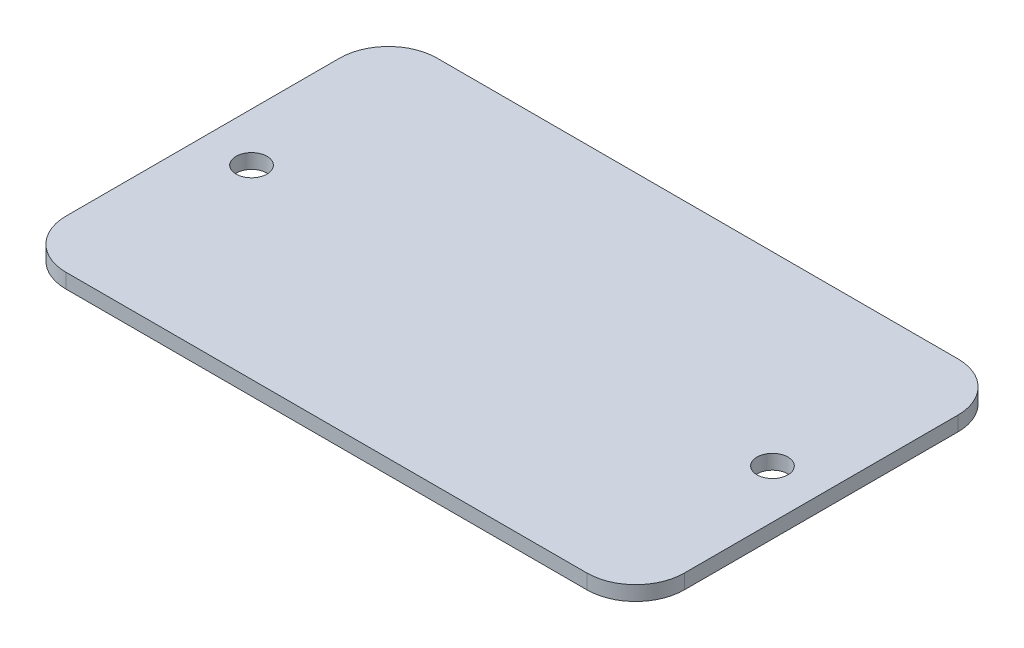
SolidWorks part; units mm, degrees
ref_plane "Front Plane" through (0, 0, 0) normal (0, 0, 1) x (1, 0, 0)
ref_plane "Top Plane" through (0, 0, 0) normal (0, 1, 0) x (1, 0, 0)
ref_plane "Right Plane" through (0, 0, 0) normal (1, 0, 0) x (0, 0, -1)
sketch "Sketch1" plane through (0, 0, 0) normal (0, 1, 0) x (1, 0, 0)
  line L1 (-53.5, -38.1) -> (53.5, -38.1)
  line L2 (-63.5, -28.1) -> (-63.5, 28.1)
  line L3 (-53.5, 38.1) -> (53.5, 38.1)
  line L4 (63.5, -28.1) -> (63.5, 28.1)
  line L5 (-63.5, -38.1) -> (63.5, 38.1) construction
  line L6 (-63.5, 38.1) -> (63.5, -38.1) construction
  arc A0 (53.5, 38.1) -> (63.5, 28.1) centre (53.5, 28.1) cw
  arc A1 (-53.5, -38.1) -> (-63.5, -28.1) centre (-53.5, -28.1) cw
  arc A2 (53.5, -38.1) -> (63.5, -28.1) centre (53.5, -28.1) ccw
  arc A3 (-63.5, 28.1) -> (-53.5, 38.1) centre (-53.5, 28.1) cw
  point P0 (0, 0)
  dimension "D3" = 10
  dimension "D1" = 127
  dimension "D2" = 76.2
extrude "Boss-Extrude1" add sketch "Sketch1" along normal blind 3
sketch "Sketch2" plane through (0, 3, 0) normal (0, 1, 0) x (1, 0, 0)
  line L0 (63.5, -28.1) -> (63.5, 28.1) construction
  line L1 (-63.5, 28.1) -> (-63.5, -28.1) construction
  circle A0 centre (-53.5, 0) radius 3.175
  circle A1 centre (53.5, 0) radius 3.175
  dimension "D1" = 6.35
  dimension "D2" = 6.35
  dimension "D3" = 10
  dimension "D4" = 10
extrude "Cut-Extrude1" cut sketch "Sketch2" against normal blind 3
